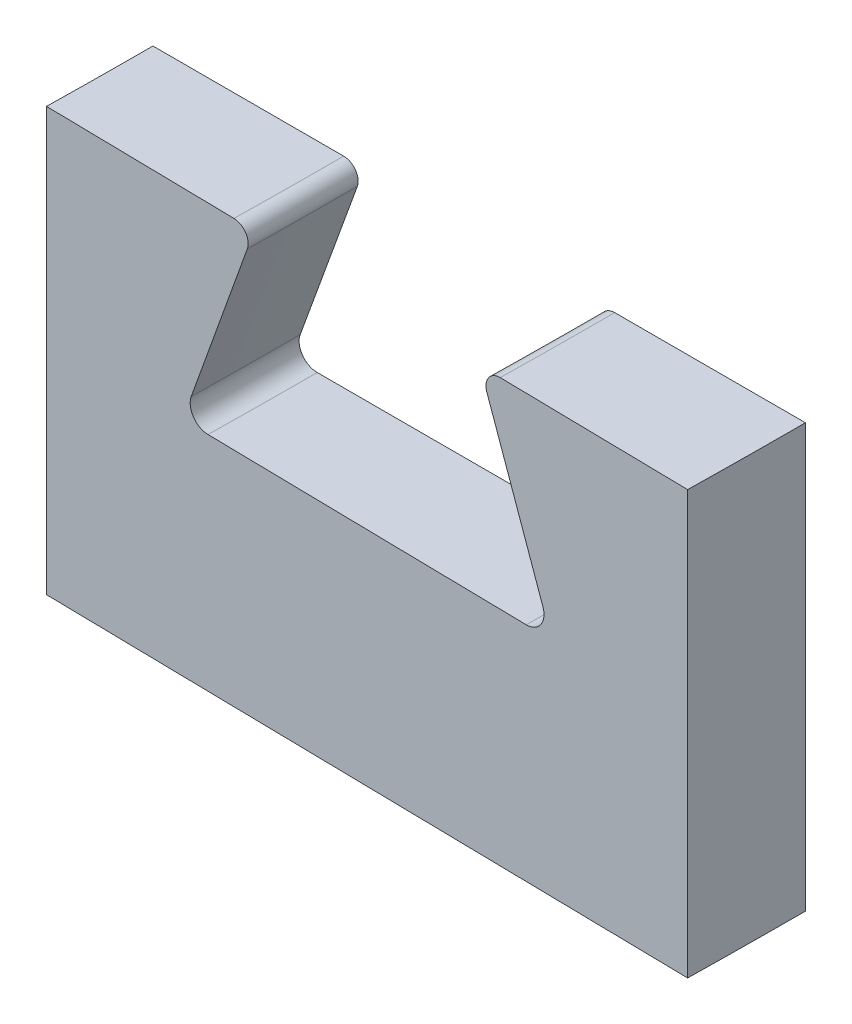
SolidWorks part; units mm, degrees
ref_plane "Front Plane" through (0, 0, 0) normal (0, 0, 1) x (1, 0, 0)
ref_plane "Top Plane" through (0, 0, 0) normal (0, 1, 0) x (1, 0, 0)
ref_plane "Right Plane" through (0, 0, 0) normal (1, 0, 0) x (0, 0, -1)
other "Configuration Table"
sketch "Sketch1" plane through (0, 0, 0) normal (0, 0, 1) x (1, 0, 0)
  line L1 (-6.858, 0) -> (6.858, 0)
  line L2 (6.858, 0) -> (6.858, 8.89)
  line L3 (6.858, 8.89) -> (2.8483, 8.89)
  line L4 (-3.4039, 4.6736) -> (3.4039, 4.6736)
  line L6 (2.5619, 8.4809) -> (3.7619, 5.1849)
  line L8 (0, 22.4622) -> (0, -12.6108) construction
  line L9 (-2.5619, 8.4809) -> (-3.7619, 5.1849)
  line L10 (-6.858, 8.89) -> (-2.8483, 8.89)
  line L11 (-6.858, 0) -> (-6.858, 8.89)
  line L12 (-133.858, 15.851) -> (-133.858, -11.3782) construction
  arc A0 (2.8483, 8.89) -> (2.5619, 8.4809) centre (2.8483, 8.5852) ccw
  arc A1 (3.7619, 5.1849) -> (3.4039, 4.6736) centre (3.4039, 5.0546) cw
  arc A2 (-3.7619, 5.1849) -> (-3.4039, 4.6736) centre (-3.4039, 5.0546) ccw
  arc A3 (-2.8483, 8.89) -> (-2.5619, 8.4809) centre (-2.8483, 8.5852) cw
  point P18 (0, 4.6736)
  point P20 (0, 0)
  dimension "D7" = 3.5076
  dimension "D8" = 0.381
  dimension "D1" = 6.858
  dimension "D2" = 8.89
  dimension "D3" = 4.0097
  dimension "D4" = 127
  dimension "D5" = 4.6736
revolve "Revolve1" add sketch "Sketch1" angle 1 about L12
